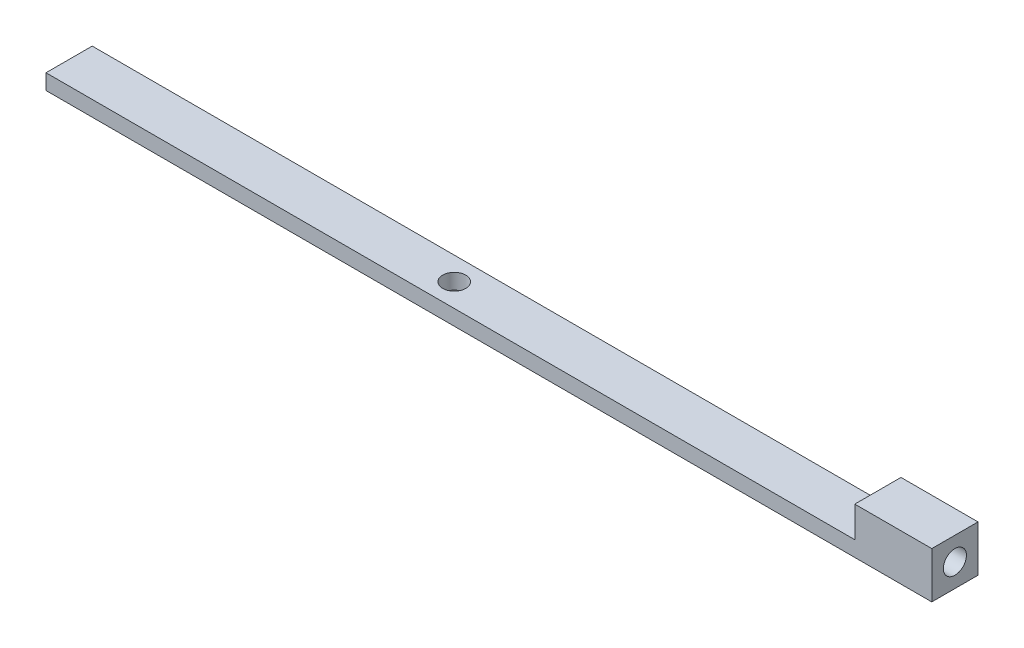
SolidWorks part; units mm, degrees
ref_plane "Front Plane" through (0, 0, 0) normal (0, 0, 1) x (1, 0, 0)
ref_plane "Top Plane" through (0, 0, 0) normal (0, 1, 0) x (1, 0, 0)
ref_plane "Right Plane" through (0, 0, 0) normal (1, 0, 0) x (0, 0, -1)
sketch "Sketch1" plane through (0, 0, 0) normal (0, 1, 0) x (1, 0, 0)
  line L1 (-62.5, 3) -> (62.5, 3)
  line L2 (-62.5, 3) -> (-62.5, -3)
  line L3 (-62.5, -3) -> (62.5, -3)
  line L4 (62.5, 3) -> (62.5, -3)
  line L5 (-62.5, 3) -> (62.5, -3) construction
  line L6 (-62.5, -3) -> (62.5, 3) construction
  point P0 (0, 0)
extrude "Boss-Extrude1" add sketch "Sketch1" along normal blind 4
sketch "Sketch2" plane through (0, 0, 0) normal (0, -1, 0) x (1, 0, 0)
  line L0 (-62.5, 0) -> (62.5, 0)
  line L1 (-62.5, -3) -> (-62.5, 3) construction
  line L2 (62.5, 3) -> (62.5, -3) construction
  circle A0 centre (0, 0) radius 1.15
extrude "Cut-Extrude1" cut sketch "Sketch2" against normal blind 4 contours A0
sketch "Sketch4" plane through (62.5, 0, 0) normal (1, 0, 0) x (0, 0, -1)
  line L2 (0, 0) -> (0, 3)
  line L3 (-3, 6) -> (3, 6)
  line L4 (-3, 6) -> (-3, 0)
  line L5 (-3, 0) -> (3, 0)
  line L6 (3, 6) -> (3, 0)
  line L7 (-3, 6) -> (3, 0) construction
  line L8 (-3, 0) -> (3, 6) construction
extrude "Boss-Extrude2" add sketch "Sketch4" along normal blind 10
sketch "Sketch5" plane through (72.5, 0, 0) normal (1, 0, 0) x (0, 0, -1)
  line L0 (0, 6) -> (0, 0)
  line L1 (-3, 6) -> (3, 6) construction
  circle A0 centre (0, 3) radius 1.25
extrude "Cut-Extrude2" cut sketch "Sketch5" against normal blind 10 contours A0
sketch "Sketch6" plane through (0, 4, 0) normal (0, 1, 0) x (1, 0, 0)
  line L1 (62.5, 3) -> (-62.5, 3)
  line L2 (62.5, 3) -> (62.5, -3)
  line L3 (62.5, -3) -> (-62.5, -3)
  line L4 (-62.5, 3) -> (-62.5, -3)
  line L5 (62.5, 3) -> (-62.5, -3) construction
  line L6 (62.5, -3) -> (-62.5, 3) construction
  point P0 (0, 0)
extrude "Cut-Extrude3" cut sketch "Sketch6" against normal blind 2
sketch "Sketch7" plane through (0, 2, 0) normal (0, 1, 0) x (1, 0, 0)
  circle A0 centre (0, 0) radius 1.5
extrude "Cut-Extrude5" cut sketch "Sketch7" against normal blind 2
sketch "Sketch8" plane through (72.5, 0, 0) normal (1, 0, 0) x (0, 0, -1)
  circle A0 centre (0, 3) radius 1.5
extrude "Cut-Extrude6" cut sketch "Sketch8" against normal blind 10
sketch "Sketch9" plane through (0, 2, 0) normal (0, 1, 0) x (1, 0, 0)
  line L0 (-62.5, 0) -> (-57.5, 0)
  line L1 (-62.5, 3) -> (-62.5, -3) construction
  circle A0 centre (-57.5, 0) radius 1.5
extrude "Cut-Extrude7" cut sketch "Sketch9" against normal blind 10 contours A0
sketch "Sketch10" plane through (-62.5, 0, 0) normal (-1, 0, 0) x (0, 0, 1)
  line L0 (0, 2) -> (0, 0)
  line L1 (-3, 2) -> (3, 2) construction
  line L3 (-3, 0) -> (3, 0)
  line L4 (-3, 0) -> (-3, 2)
  line L5 (-3, 2) -> (3, 2)
  line L6 (3, 0) -> (3, 2)
  line L7 (-3, 0) -> (3, 2) construction
  line L8 (-3, 2) -> (3, 0) construction
  point P5 (0, 1)
extrude "Cut-Extrude8" cut sketch "Sketch10" against normal blind 20 contours L4 L5 L6 L3
sketch "Sketch11" plane through (0, 2, 0) normal (0, 1, 0) x (1, 0, 0)
  circle A0 centre (0, 0) radius 1.5
extrude "Boss-Extrude3" add sketch "Sketch11" against normal blind 2
sketch "Sketch12" plane through (0, 2, 0) normal (0, 1, 0) x (1, 0, 0)
  line L0 (-42.5, 0) -> (7.5, 0)
  line L1 (-42.5, 3) -> (-42.5, -3) construction
  circle A0 centre (7.5, 0) radius 1.5
extrude "Cut-Extrude9" cut sketch "Sketch12" against normal blind 2 contours A0
